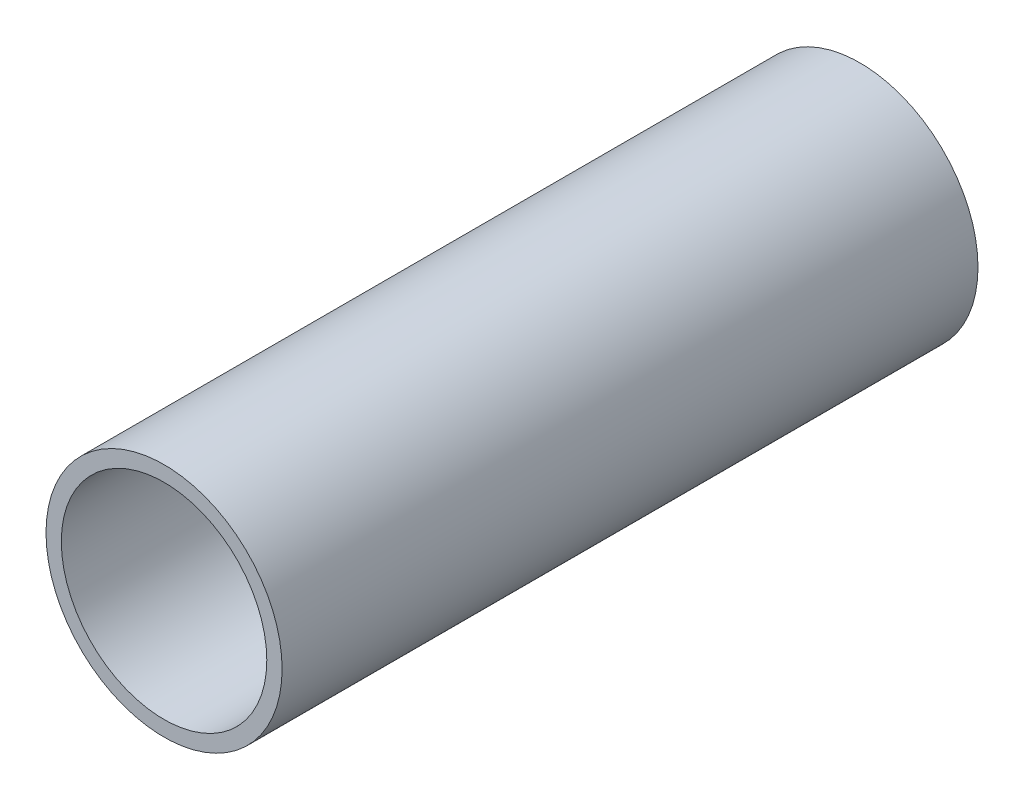
SolidWorks part; units mm, degrees
ref_plane "Front Plane" through (0, 0, 0) normal (0, 0, 1) x (1, 0, 0)
ref_plane "Top Plane" through (0, 0, 0) normal (0, 1, 0) x (1, 0, 0)
ref_plane "Right Plane" through (0, 0, 0) normal (1, 0, 0) x (0, 0, -1)
sketch "Sketch1" plane through (0, 0, 0) normal (0, 0, 1) x (1, 0, 0)
  circle A0 centre (0, 0) radius 30.1625
  circle A1 centre (0, 0) radius 26.2509
  dimension "D1" = 60.325
  dimension "D2" = 3.9116
extrude "Boss-Extrude1" add sketch "Sketch1" along normal blind 177.8
